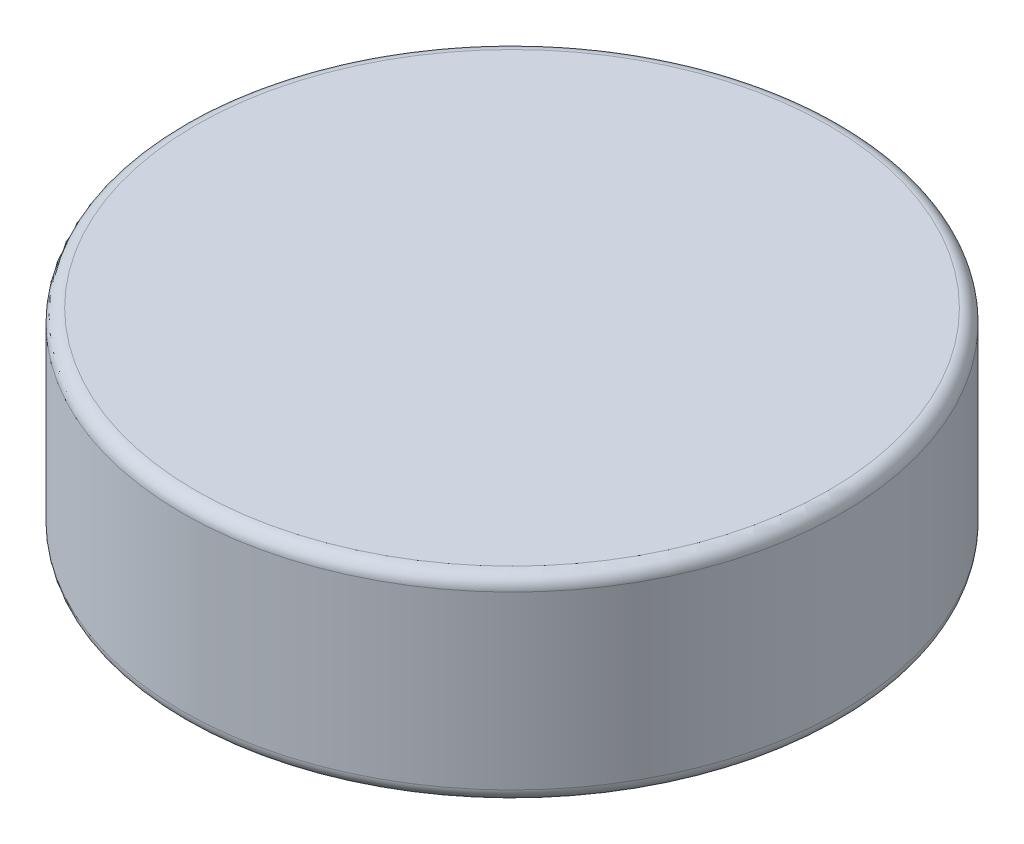
SolidWorks part; units mm, degrees
ref_plane "Front" through (0, 0, 0) normal (0, 0, 1) x (1, 0, 0)
ref_plane "Top" through (0, 0, 0) normal (0, 1, 0) x (1, 0, 0)
ref_plane "Right" through (0, 0, 0) normal (1, 0, 0) x (0, 0, -1)
sketch "Эскиз1" plane through (0, 0, 0) normal (0, 1, 0) x (1, 0, 0)
  circle A0 centre (0, 0) radius 5
  dimension "D1" = 10
extrude "Бобышка-Вытянуть1" add sketch "Эскиз1" along normal blind 3
fillet "Скругление1" radius 0.2 2 edges at (0, 0, 5) (0, 3, 5)
